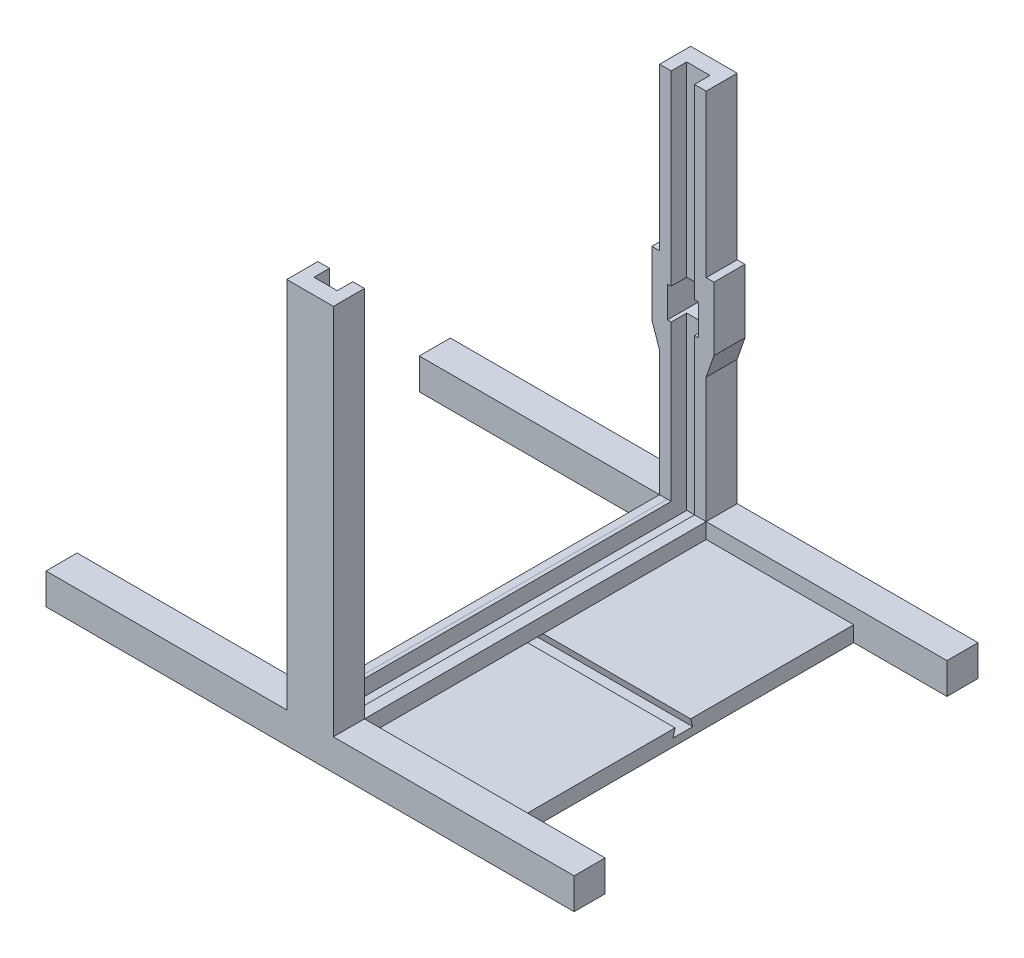
SolidWorks part; units mm, degrees
ref_plane "Front Plane" through (0, 0, 0) normal (0, 0, 1) x (1, 0, 0)
ref_plane "Top Plane" through (0, 0, 0) normal (0, 1, 0) x (1, 0, 0)
ref_plane "Right Plane" through (0, 0, 0) normal (1, 0, 0) x (0, 0, -1)
sketch "Sketch1" plane through (0, 0, 0) normal (0, 0, 1) x (1, 0, 0)
  line L0 (0, 0) -> (215.7049, 0)
  line L1 (215.7049, 0) -> (215.7049, 12.7)
  line L2 (215.7049, 12.7) -> (114.1049, 12.7)
  line L3 (114.1049, 12.7) -> (114.1049, 165.1)
  line L4 (114.1049, 165.1) -> (101.4049, 165.1)
  line L5 (101.4049, 165.1) -> (101.4049, 12.7)
  line L6 (101.4049, 12.7) -> (0, 12.7)
  line L7 (0, 12.7) -> (0, 0)
  dimension "D1" = 101.4049
  dimension "D2" = 114.1049
  dimension "D3" = 215.7049
  dimension "D4" = 165.1
extrude "Boss-Extrude2" add sketch "Sketch1" along normal blind 6.35 contours L7 L0 L1 L2 L3 L4 L5 L6
sketch "Sketch2" plane through (0, 0, 6.35) normal (0, 0, 1) x (1, 0, 0)
  line L0 (101.4049, 12.7) -> (101.4049, 6.35)
  line L1 (101.4049, 6.35) -> (102.9924, 6.35)
  line L2 (102.9924, 6.35) -> (102.9924, 165.1)
  line L3 (114.1049, 165.1) -> (101.4049, 165.1) construction
  line L4 (102.9924, 165.1) -> (101.4049, 165.1)
  line L5 (101.4049, 165.1) -> (101.4049, 12.7) construction
  line L6 (101.4049, 165.1) -> (101.4049, 12.7)
extrude "Boss-Extrude3" add sketch "Sketch2" along normal blind 6.35
sketch "Sketch3" plane through (0, 0, 6.35) normal (0, 0, 1) x (1, 0, 0)
  line L1 (114.1049, 165.1) -> (112.5174, 165.1)
  line L2 (114.1049, 165.1) -> (114.1049, 6.35)
  line L4 (114.1049, 6.35) -> (112.5174, 6.35)
  line L5 (112.5174, 165.1) -> (112.5174, 6.35)
extrude "Boss-Extrude4" add sketch "Sketch3" along normal blind 6.35
sketch "Sketch4" plane through (0, 0, 6.35) normal (0, 0, 1) x (1, 0, 0)
  line L1 (0, 0) -> (215.7049, 0) construction
  line L2 (101.4049, 6.35) -> (114.1049, 6.35)
  line L3 (101.4049, 6.35) -> (101.4049, 0)
  line L4 (101.4049, 0) -> (114.1049, 0)
  line L5 (114.1049, 6.35) -> (114.1049, 0)
extrude "Boss-Extrude5" add sketch "Sketch4" along normal blind 158.75 contours L3 L2 L5 L4
sketch "Sketch5" plane through (0, 6.35, 0) normal (0, 1, 0) x (1, 0, 0)
  line L0 (114.1049, -165.1) -> (114.1049, -12.7) construction
  line L1 (101.4049, -165.1) -> (114.1049, -165.1)
  line L2 (101.4049, -165.1) -> (101.4049, -158.75)
  line L3 (101.4049, -158.75) -> (114.1049, -158.75)
  line L4 (114.1049, -165.1) -> (114.1049, -158.75)
extrude "Boss-Extrude6" add sketch "Sketch5" along normal blind 158.75
sketch "Sketch6" plane through (0, 0, 158.75) normal (0, 0, -1) x (-1, 0, 0)
  line L1 (-101.4049, 6.35) -> (-102.9924, 6.35)
  line L2 (-101.4049, 6.35) -> (-101.4049, 165.1)
  line L3 (-101.4049, 165.1) -> (-102.9924, 165.1)
  line L4 (-102.9924, 6.35) -> (-102.9924, 165.1)
extrude "Boss-Extrude7" add sketch "Sketch6" along normal blind 6.35
sketch "Sketch7" plane through (0, 0, 158.75) normal (0, 0, -1) x (-1, 0, 0)
  line L1 (-114.1049, 6.35) -> (-112.5174, 6.35)
  line L2 (-114.1049, 6.35) -> (-114.1049, 165.1)
  line L3 (-114.1049, 165.1) -> (-112.5174, 165.1)
  line L4 (-112.5174, 6.35) -> (-112.5174, 165.1)
extrude "Boss-Extrude8" add sketch "Sketch7" along normal blind 6.35
sketch "Sketch8" plane through (0, 0, 152.4) normal (0, 0, -1) x (-1, 0, 0)
  line L2 (-112.5174, 6.35) -> (-112.5174, 165.1) construction
  line L3 (-114.1049, 6.35) -> (-112.5174, 6.35)
  line L4 (-114.1049, 6.35) -> (-114.1049, 12.7)
  line L5 (-114.1049, 12.7) -> (-112.5174, 12.7)
  line L6 (-112.5174, 6.35) -> (-112.5174, 12.7)
extrude "Boss-Extrude9" add sketch "Sketch8" along normal blind 139.7
sketch "Sketch10" plane through (0, 0, 12.7) normal (0, 0, 1) x (1, 0, 0)
  line L1 (101.4049, 6.35) -> (102.9924, 6.35)
  line L2 (101.4049, 6.35) -> (101.4049, 12.7)
  line L3 (101.4049, 12.7) -> (102.9924, 12.7)
  line L4 (102.9924, 6.35) -> (102.9924, 12.7)
extrude "Boss-Extrude10" add sketch "Sketch10" along normal blind 139.7
sketch "Sketch11" plane through (101.4049, 0, 0) normal (-1, 0, 0) x (0, 0, 1)
  line L1 (165.1, 0) -> (152.4, 0)
  line L2 (165.1, 0) -> (165.1, 12.6998)
  line L3 (165.1, 12.6998) -> (152.4, 12.6998)
  line L4 (152.4, 0) -> (152.4, 12.6998)
  dimension "D1" = 12.7
extrude "Boss-Extrude11" add sketch "Sketch11" along normal blind 101.6 contours L2 L1 L4 L3
sketch "Sketch12" plane through (0, 0, 6.35) normal (0, 0, 1) x (1, 0, 0)
  line L1 (0, 0) -> (101.4049, 0)
  line L2 (0, 0) -> (0, 12.7)
  line L3 (0, 12.7) -> (101.4049, 12.7)
  line L4 (101.4049, 0) -> (101.4049, 12.7)
extrude "Boss-Extrude12" add sketch "Sketch12" along normal blind 6.35
sketch "Sketch13" plane through (0, 0, 6.35) normal (0, 0, 1) x (1, 0, 0)
  line L1 (114.1049, 0) -> (215.7049, 0)
  line L2 (114.1049, 0) -> (114.1049, 12.7)
  line L3 (114.1049, 12.7) -> (215.7049, 12.7)
  line L4 (215.7049, 0) -> (215.7049, 12.7)
extrude "Boss-Extrude13" add sketch "Sketch13" along normal blind 6.35
sketch "Sketch14" plane through (114.1049, 0, 0) normal (1, 0, 0) x (0, 0, -1)
  line L1 (-165.1, 0) -> (-152.4, 0)
  line L2 (-165.1, 0) -> (-165.1, 12.7)
  line L3 (-165.1, 12.7) -> (-152.4, 12.7)
  line L4 (-152.4, 0) -> (-152.4, 12.7)
extrude "Boss-Extrude14" add sketch "Sketch14" along normal blind 101.6
sketch "Sketch15" plane through (114.1049, 0, 0) normal (1, 0, 0) x (0, 0, -1)
  line L1 (-152.4, 0) -> (-12.7, 0)
  line L2 (-152.4, 0) -> (-152.4, 6.35)
  line L3 (-152.4, 6.35) -> (-12.7, 6.35)
  line L4 (-12.7, 0) -> (-12.7, 6.35)
extrude "Boss-Extrude15" add sketch "Sketch15" along normal blind 63.5
sketch "Sketch16" plane through (0, 6.35, 0) normal (0, 1, 0) x (1, 0, 0)
  line L0 (177.6049, -12.7) -> (177.6049, -152.4) construction
  line L1 (177.6049, -82.55) -> (177.6049, -79.375)
  line L2 (177.6049, -79.375) -> (114.1049, -79.375)
  line L4 (114.1049, -79.375) -> (114.1049, -82.55)
  line L5 (114.1049, -12.7) -> (114.1049, -152.4) construction
  line L6 (114.1049, -82.55) -> (114.1049, -85.725)
  line L7 (114.1049, -12.7) -> (114.1049, -152.4) construction
  line L8 (114.1049, -85.725) -> (177.6049, -85.725)
  line L9 (177.6049, -85.725) -> (177.6049, -82.55)
extrude "Cut-Extrude1" cut sketch "Sketch16" against normal blind 3.175 draft 15 draft outward yes
sketch "Sketch17" plane through (0, 0, 0) normal (0, 0, -1) x (-1, 0, 0)
  line L8 (-107.8037, 87.3125) -> (-112.5662, 87.3125)
  line L9 (-112.5662, 82.55) -> (-112.5662, 87.3125)
  line L10 (-107.8037, 87.3125) -> (-103.0412, 87.3125)
  line L13 (-103.0412, 87.3125) -> (-103.0412, 82.55)
  line L15 (-103.0412, 82.55) -> (-103.0412, 77.7847)
  line L16 (-103.0412, 77.7847) -> (-107.8065, 77.7847)
  line L18 (-107.8065, 77.7847) -> (-112.5662, 77.7847)
  line L21 (-112.5662, 77.7847) -> (-112.5662, 82.55)
extrude "Cut-Extrude3" cut sketch "Sketch17" against normal blind 6.35
sketch "Sketch18" plane through (101.4049, 0, 0) normal (-1, 0, 0) x (0, 0, 1)
  line L1 (0, 12.7) -> (12.7, 12.7)
  line L2 (0, 12.7) -> (0, 165.1)
  line L3 (0, 165.1) -> (12.7, 165.1)
  line L4 (12.7, 12.7) -> (12.7, 165.1)
  dimension "D1" = 152.4
  dimension "D2" = 12.7
extrude "Boss-Extrude17" add sketch "Sketch18" along normal blind 3.175
sketch "Sketch19" plane through (114.1049, 0, 0) normal (1, 0, 0) x (0, 0, -1)
  line L1 (-12.7, 12.7) -> (0, 12.7)
  line L2 (-12.7, 12.7) -> (-12.7, 165.1)
  line L3 (-12.7, 165.1) -> (0, 165.1)
  line L4 (0, 12.7) -> (0, 165.1)
  dimension "D1" = 152.4
  dimension "D2" = 12.7
extrude "Boss-Extrude18" add sketch "Sketch19" along normal blind 3.175
sketch "Sketch20" plane through (101.4049, 0, 0) normal (-1, 0, 0) x (0, 0, 1)
  line L1 (152.4, 12.7) -> (165.1, 12.7)
  line L2 (152.4, 12.7) -> (152.4, 165.1)
  line L3 (152.4, 165.1) -> (165.1, 165.1)
  line L4 (165.1, 12.7) -> (165.1, 165.1)
  dimension "D1" = 152.4
  dimension "D2" = 12.7
extrude "Boss-Extrude19" add sketch "Sketch20" along normal blind 3.175
sketch "Sketch21" plane through (114.1049, 0, 0) normal (1, 0, 0) x (0, 0, -1)
  line L1 (-165.1, 12.7) -> (-152.4, 12.7)
  line L2 (-165.1, 12.7) -> (-165.1, 165.1)
  line L3 (-165.1, 165.1) -> (-152.4, 165.1)
  line L4 (-152.4, 12.7) -> (-152.4, 165.1)
  dimension "D1" = 152.4
  dimension "D2" = 12.7
extrude "Boss-Extrude20" add sketch "Sketch21" along normal blind 3.175
sketch "Sketch22" plane through (114.1049, 0, 0) normal (1, 0, 0) x (0, 0, -1)
  line L1 (-152.4, 6.35) -> (-12.7, 6.35)
  line L2 (-152.4, 6.35) -> (-152.4, 12.7)
  line L3 (-152.4, 12.7) -> (-12.7, 12.7)
  line L4 (-12.7, 6.35) -> (-12.7, 12.7)
  dimension "D1" = 6.35
  dimension "D2" = 139.7
extrude "Boss-Extrude21" add sketch "Sketch22" along normal blind 3.175
sketch "Sketch23" plane through (101.4049, 0, 0) normal (-1, 0, 0) x (0, 0, 1)
  line L1 (12.7, 0) -> (152.4, 0)
  line L2 (12.7, 0) -> (12.7, 12.6998)
  line L3 (12.7, 12.6998) -> (152.4, 12.6998)
  line L4 (152.4, 0) -> (152.4, 12.6998)
  dimension "D1" = 12.6998
  dimension "D2" = 139.7
extrude "Boss-Extrude22" add sketch "Sketch23" along normal blind 3.175
sketch "Sketch25" plane through (0, 0, 0) normal (0, 0, -1) x (-1, 0, 0)
  line L1 (-112.5662, 88.9) -> (-101.4537, 88.9)
  line L2 (-101.4537, 88.9) -> (-101.4537, 76.2)
  line L3 (-101.4537, 76.2) -> (-114.1537, 76.2)
  line L4 (-114.1537, 76.2) -> (-114.1537, 88.9)
  line L5 (-114.1537, 88.9) -> (-112.5662, 88.9)
  dimension "D3" = 12.7
  dimension "D4" = 12.7
  dimension "D5" = 12.7
extrude "Cut-Extrude4" cut sketch "Sketch25" against normal blind 12.7
sketch "Sketch30" plane through (117.2799, 0, 0) normal (1, 0, 0) x (0, 0, -1)
  line L1 (0, 12.7) -> (0, 165.1) construction
  line L2 (0, 73.025) -> (0, 99.06)
  line L3 (0, 99.06) -> (-12.7, 99.06)
  line L5 (-12.7, 99.06) -> (-12.7, 73.025)
  line L6 (-12.7, 165.1) -> (-12.7, 12.7) construction
  line L7 (-12.7, 73.025) -> (0, 73.025)
  dimension "D3" = 12.7
extrude "Boss-Extrude25" add sketch "Sketch30" along normal blind 3.175
sketch "Sketch31" plane through (98.2299, 0, 0) normal (-1, 0, 0) x (0, 0, 1)
  line L1 (0, 165.1) -> (0, 12.7) construction
  line L2 (0, 73.025) -> (0, 99.06)
  line L3 (0, 99.06) -> (12.7, 99.06)
  line L4 (12.7, 99.06) -> (12.7, 73.025)
  line L5 (12.7, 12.7) -> (12.7, 165.1) construction
  line L6 (12.7, 73.025) -> (0, 73.025)
  dimension "D5" = 12.7
extrude "Boss-Extrude26" add sketch "Sketch31" along normal blind 3.175
sketch "Sketch32" plane through (0, 0, 0) normal (0, 0, -1) x (-1, 0, 0)
  line L0 (-120.4549, 73.025) -> (-117.2799, 63.8401)
  line L1 (-117.2799, 12.7) -> (-117.2799, 73.025) construction
  line L2 (-117.2799, 63.8401) -> (-117.2799, 73.025)
  line L3 (-117.2799, 73.025) -> (-120.4549, 73.025)
  dimension "D1" = 9.7182
  dimension "D2" = 9.1849
  dimension "D3" = 3.175
extrude "Boss-Extrude27" add sketch "Sketch32" against normal blind 12.7
sketch "Sketch36" plane through (0, 0, 0) normal (0, 0, -1) x (-1, 0, 0)
  line L0 (-95.0549, 73.025) -> (-98.2299, 63.9112)
  line L1 (-98.2299, 73.025) -> (-98.2299, 12.7) construction
  line L2 (-95.0549, 73.025) -> (-98.2299, 73.025)
  line L3 (-98.2299, 73.025) -> (-98.2299, 63.9112)
  dimension "D1" = 9.651
  dimension "D2" = 3.175
  dimension "D3" = 9.1138
extrude "Boss-Extrude28" add sketch "Sketch36" against normal blind 12.7
sketch "Sketch37" plane through (0, 0, 0) normal (0, 0, -1) x (-1, 0, 0)
  circle A0 centre (-117.8037, 82.55) radius 0.635
  circle A1 centre (-96.8037, 82.55) radius 0.635
  circle A2 centre (-96.8037, 94.55) radius 0.635
  circle A3 centre (-117.8037, 94.55) radius 0.635
extrude "Boss-Extrude29" add sketch "Sketch37" along normal blind 7.9375
sketch "Sketch38" plane through (0, 0, -7.9375) normal (0, 0, -1) x (-1, 0, 0)
  circle A0 centre (-117.8037, 94.55) radius 0.635
extrude "Cut-Extrude5" cut sketch "Sketch38" against normal blind 8.4455
sketch "Sketch39" plane through (0, 0, -7.9375) normal (0, 0, -1) x (-1, 0, 0)
  circle A0 centre (-96.8037, 94.55) radius 0.635
extrude "Cut-Extrude6" cut sketch "Sketch39" against normal blind 8.4455 contours A0
sketch "Sketch40" plane through (0, 0, -7.9375) normal (0, 0, -1) x (-1, 0, 0)
  circle A0 centre (-117.8037, 82.55) radius 0.635
extrude "Cut-Extrude7" cut sketch "Sketch40" against normal blind 8.4455
sketch "Sketch41" plane through (0, 0, -7.9375) normal (0, 0, -1) x (-1, 0, 0)
  circle A0 centre (-96.8037, 82.55) radius 0.635
extrude "Cut-Extrude8" cut sketch "Sketch41" against normal blind 8.4455
